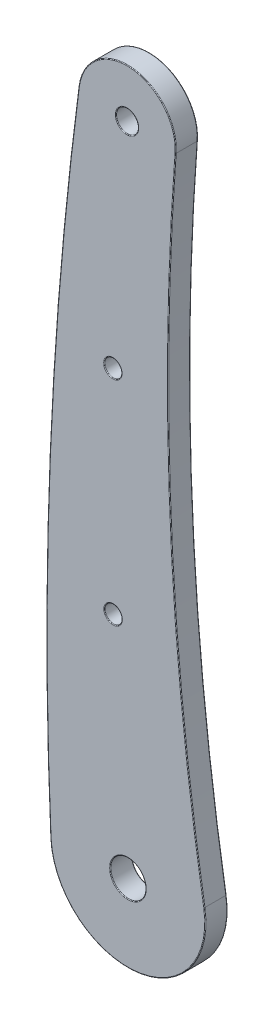
SolidWorks part; units mm, degrees
ref_plane "Front Plane" through (0, 0, 0) normal (0, 0, 1) x (1, 0, 0)
ref_plane "Top Plane" through (0, 0, 0) normal (0, 1, 0) x (1, 0, 0)
ref_plane "Right Plane" through (0, 0, 0) normal (1, 0, 0) x (0, 0, -1)
sketch "Sketch7" plane through (0, 0, 0) normal (0, 0, 1) x (1, 0, 0)
  line L0 (-15.8997, 190.6583) -> (-16.0954, 338.6582) construction
  line L1 (-15.8997, 190.6583) -> (-16.0954, 338.6582) construction
  circle A0 centre (-16.0954, 338.6582) radius 11 construction
  circle A1 centre (-15.8997, 190.6583) radius 17.5 construction
  circle A2 centre (-16.0954, 338.6582) radius 11 construction
  circle A3 centre (-15.8997, 190.6583) radius 17.5 construction
  circle A4 centre (-16.0954, 338.6582) radius 2.5
  circle A5 centre (-15.8997, 190.6583) radius 4
  arc A6 (-5.1269, 337.8261) -> (1.3609, 193.5428) centre (593.1541, 292.4409) ccw
  arc A7 (-27.0011, 340.0952) -> (-33.3811, 189.8512) centre (815.7145, 229.0527) ccw
  arc A8 (-16.0954, 338.6582) -> (-15.8997, 190.6583) centre (730.3422, 265.6451) ccw construction
  arc A9 (-33.3811, 189.8512) -> (1.3609, 193.5428) centre (-15.8997, 190.6583) ccw
  arc A10 (-27.0011, 340.0952) -> (-5.1269, 337.8261) centre (-16.0954, 338.6582) cw
  point P17 (-19.3012, 288.7703)
  point P18 (-19.2414, 240.6583)
  dimension "D1" = 5
  dimension "D2" = 8
  dimension "D3" = 850
  dimension "D4" = 600
  dimension "D5" = 750
  dimension "D6" = 50
  dimension "D7" = 50
extrude "Boss-Extrude1" add sketch "Sketch7" against normal blind 5
hole_wizard "M3.5 Clearance Hole1" positions "Sketch10" profile "Sketch11" hole size "M3.5" standard "ISO"
sketch "Sketch10" plane through (0, 0, 0) normal (0, 0, 1) x (1, 0, 0)
  point P0 (-19.2414, 240.6583)
  point P3 (-19.3012, 288.7703)
sketch "Sketch11" plane through (-19.2414, 240.6583, 0) normal (1, 0, 0) x (0, -1, 0)
  line L0 (0, 0) -> (0, 11.1717)
  line L1 (0, 11.1717) -> (1.95, 10)
  line L2 (1.95, 10) -> (1.95, 0)
  line L5 (1.95, 0) -> (0, 0)
  line L10 (0, 11.1717) -> (-1.95, 10) construction
  line L11 (0, -6.35) -> (0, 107.95) construction
  dimension "Hole Dia." = 3.9
  dimension "Hole Depth" = 10
  dimension "Drill Angle" = 118
fillet "Fillet1" radius 0.15 16 edges at (-33.5202, 265.1146, -5) (-14.0506, 173.2563, -5) (-6.2402, 265.4885, -5) (-14.9604, 349.5994, -5) (-13.5954, 338.6582, -5) (-11.8997, 190.6583, -5) (-21.2512, 288.7703, -5) (-21.1914, 240.6583, -5) (-6.2402, 265.4885, 0) (-14.0506, 173.2563, 0) (-33.5202, 265.1146, 0) (-14.9604, 349.5994, 0) (-13.5954, 338.6582, 0) (-11.8997, 190.6583, 0) (-17.3512, 288.7703, 0) (-17.2914, 240.6583, 0)
